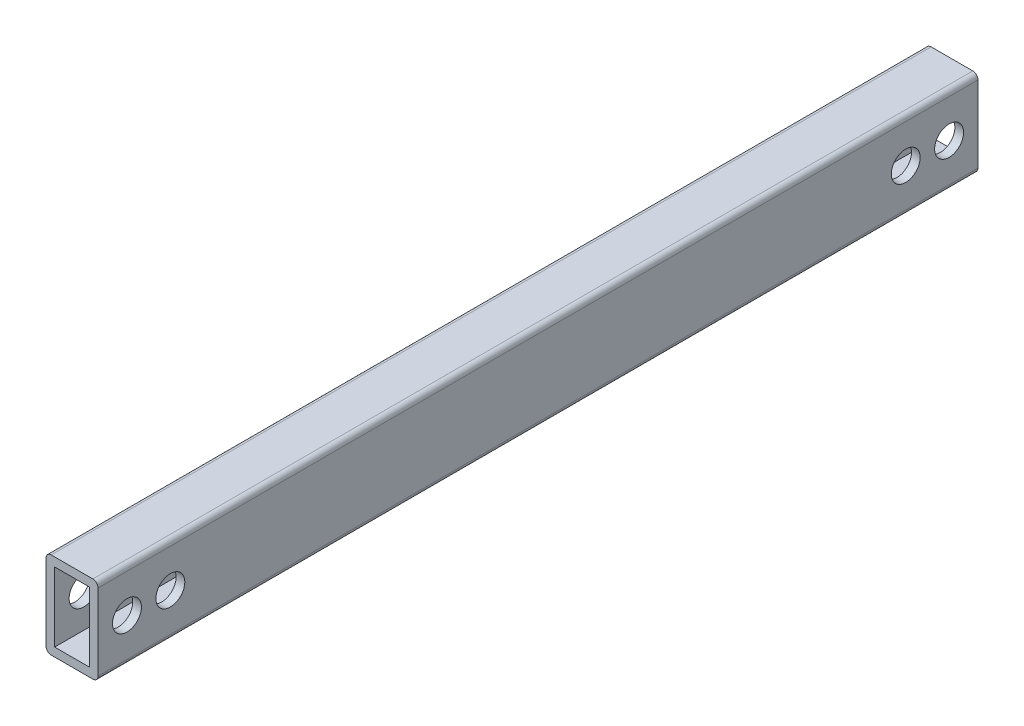
SolidWorks part; units mm, degrees
material "6061-T6 (SS)"
ref_plane "Front Plane" through (0, 0, 0) normal (0, 0, 1) x (1, 0, 0)
ref_plane "Top Plane" through (0, 0, 0) normal (0, 1, 0) x (1, 0, 0)
ref_plane "Right Plane" through (0, 0, 0) normal (1, 0, 0) x (0, 0, -1)
sketch "Sketch1" plane through (0, 0, 0) normal (0, 0, 1) x (1, 0, 0)
  line L1 (9, -15) -> (-9, -15)
  line L2 (9, -15) -> (9, 15)
  line L3 (9, 15) -> (-9, 15)
  line L4 (-9, -15) -> (-9, 15)
  line L5 (9, -15) -> (-9, 15) construction
  line L6 (9, 15) -> (-9, -15) construction
  line L7 (6, -12) -> (-6, -12)
  line L8 (6, -12) -> (6, 12)
  line L9 (6, 12) -> (-6, 12)
  line L10 (-6, -12) -> (-6, 12)
  line L11 (6, -12) -> (-6, 12) construction
  line L12 (6, 12) -> (-6, -12) construction
  point P0 (0, 0)
  point P6 (0, 0)
  dimension "D1" = 30
  dimension "D2" = 18
  dimension "D3" = 3
  dimension "D4" = 3
extrude "Body" add sketch "Sketch1" along normal blind 304.3179
sketch "Sketch2" plane through (9, 0, 0) normal (1, 0, 0) x (0, 0, -1)
  line L0 (0, 0) -> (-304.3179, 0) construction
  line L1 (-304.3179, -15) -> (-304.3179, 15) construction
  line L2 (-152.159, -15) -> (-152.159, 15) construction
  line L3 (-304.3179, -15) -> (0, -15) construction
  line L4 (-304.3179, 15) -> (0, 15) construction
  circle A0 centre (-294.3179, 0) radius 5
  circle A1 centre (-279.3179, 0) radius 5
  circle A2 centre (-25, 0) radius 5
  circle A3 centre (-10, 0) radius 5
  dimension "D1" = 10
  dimension "D2" = 10
  dimension "D3" = 10
  dimension "D4" = 15
extrude "Mount Holes" cut sketch "Sketch2" against normal through all
fillet "Corner Fillets" radius 1.8 4 edges at (-9, -15, 152.159) (9, -15, 152.159) (9, 15, 152.159) (-9, 15, 152.159)
equation "\"linkage_thickness\"= 18.0mm"
equation "\"width\"= 30.0mm"
equation "\"wall_thickness\"= 3.0mm"
equation "\"length\"= 304.3179046755698mm"
equation "\"angle\"= 48.83451044543235"
equation "\"bolt_diameter\"= 10.0mm"
equation "\"bolt_spacing\"= 5.0mm"
equation "\"D1@Sketch1\"=\"width\""
equation "\"D2@Sketch1\"=\"linkage_thickness\""
equation "\"D3@Sketch1\"=\"wall_thickness\""
equation "\"D4@Sketch1\"=\"wall_thickness\""
equation "\"D1@Body\"=\"length\""
equation "\"D1@Sketch2\"=\"bolt_diameter\""
equation "\"D2@Sketch2\"=\"bolt_diameter\""
equation "\"D3@Sketch2\"=\"bolt_spacing\"+\"bolt_diameter\"/2"
equation "\"D4@Sketch2\"=\"bolt_spacing\"+\"bolt_diameter\""
equation "\"D1@Corner Fillets\"=\"linkage_thickness\"/10"
